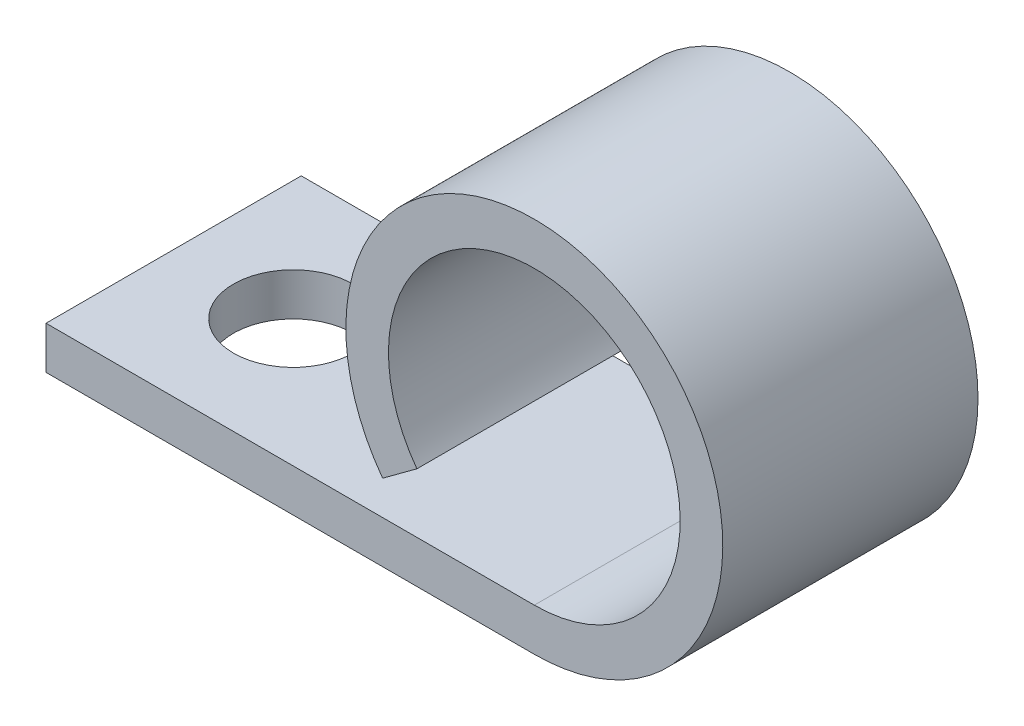
SolidWorks part; units mm, degrees
ref_plane "Front Plane" through (0, 0, 0) normal (0, 0, 1) x (1, 0, 0)
ref_plane "Top Plane" through (0, 0, 0) normal (0, 1, 0) x (1, 0, 0)
ref_plane "Right Plane" through (0, 0, 0) normal (1, 0, 0) x (0, 0, -1)
sketch "Sketch1" plane through (0, 0, 0) normal (0, 0, 1) x (1, 0, 0)
  line L0 (-21.2598, -8.2042) -> (0, -8.2042)
  line L1 (-21.2598, -8.2042) -> (-21.2598, -6.35)
  line L2 (-21.2598, -6.35) -> (0, -6.35)
  line L3 (-6.6049, -4.8666) -> (-5.1122, -3.7667)
  line L4 (0, 0) -> (0, -6.35) construction
  circle A0 centre (0, 0) radius 6.35 construction
  arc A1 (0, -8.2042) -> (-6.6049, -4.8666) centre (0, 0) ccw
  arc A2 (0, -6.35) -> (-5.1122, -3.7667) centre (0, 0) ccw
  dimension "Diameter" = 12.7
  dimension "thickness" = 1.8542
  dimension "Length" = 29.464
  dimension "D1" = 1.4834
extrude "Boss-Extrude1" add sketch "Sketch1" along normal mid plane 11.1125
sketch "Sketch2" plane through (0, -6.35, 0) normal (0, 1, 0) x (1, 0, 0)
  line L0 (-16.0528, 0) -> (0, 0) construction
  line L1 (-21.2598, -5.5562) -> (-21.2598, 5.5562) construction
  circle A0 centre (-16.0528, 0) radius 2.6035
  dimension "Hole Diameter" = 5.207
  dimension "D2" = 5.207
extrude "Cut-Extrude1" cut sketch "Sketch2" against normal through all
equation "\"D2@Sketch2\"=\"Hole Diameter@Sketch2\""
equation "\"D1@Sketch1\"=\"thickness@Sketch1\"*.8"
